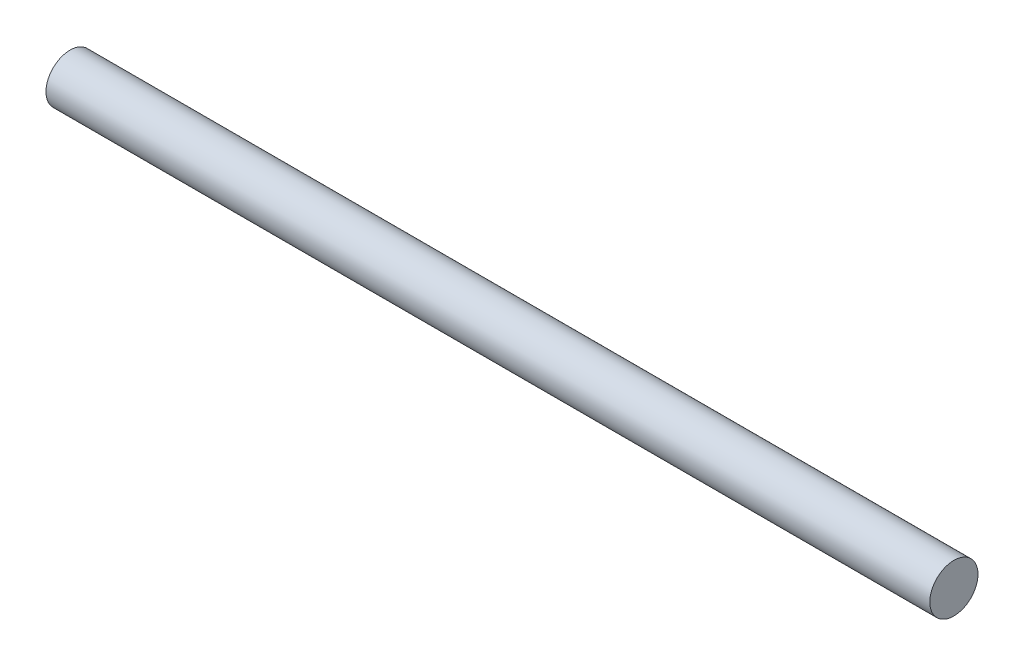
SolidWorks part; units mm, degrees
material "AISI 304"
ref_plane "Front Plane" through (0, 0, 0) normal (0, 0, 1) x (1, 0, 0)
ref_plane "Top Plane" through (0, 0, 0) normal (0, 1, 0) x (1, 0, 0)
ref_plane "Right Plane" through (0, 0, 0) normal (1, 0, 0) x (0, 0, -1)
sketch "Sketch1" plane through (0, 0, 0) normal (1, 0, 0) x (0, 0, -1)
  circle A0 centre (0, 0) radius 1.5
  dimension "D1" = 3
extrude "Boss-Extrude1" add sketch "Sketch1" along normal blind 55
